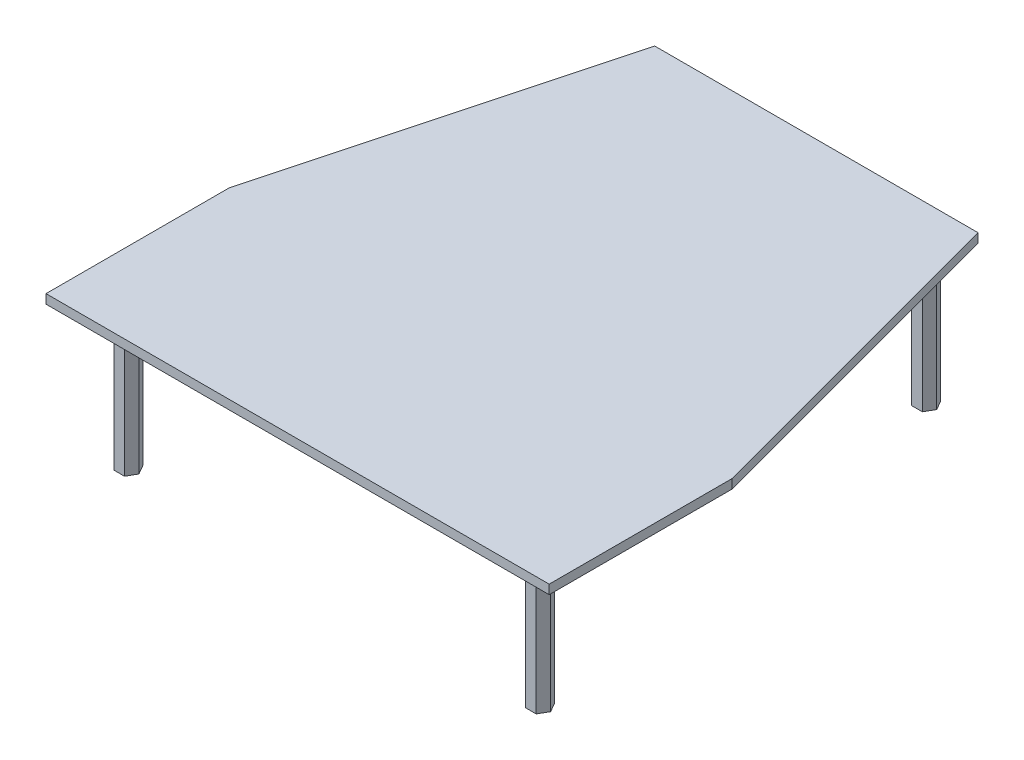
SolidWorks part; units mm, degrees
ref_plane "前视基准面" through (0, 0, 0) normal (0, 0, 1) x (1, 0, 0)
ref_plane "上视基准面" through (0, 0, 0) normal (0, 1, 0) x (1, 0, 0)
ref_plane "右视基准面" through (0, 0, 0) normal (1, 0, 0) x (0, 0, -1)
sketch "草图1" plane through (0, 0, 0) normal (0, 1, 0) x (1, 0, 0)
  line L0 (0, 0) -> (0, 262.6348) construction
  line L2 (-55, 0) -> (-55, 40)
  line L3 (-55, 40) -> (-35.3298, 113.4104)
  line L4 (-35.3298, 113.4104) -> (35.3298, 113.4104)
  line L15 (55, 40) -> (35.3298, 113.4104)
  line L16 (55, 0) -> (55, 40)
  line L17 (-55, 0) -> (55, 0)
  dimension "D1" = 15
  dimension "D3" = 110
  dimension "D4" = 76
  dimension "D5" = 40
extrude "凸台-拉伸1" add sketch "草图1" along normal mid plane 2
sketch "草图2" plane through (0, -1, 0) normal (0, -1, 0) x (1, 0, 0)
  line L0 (0, 0) -> (0, -113.4104) construction
  line L1 (-42.6906, -8) -> (-43.8453, -6)
  line L2 (-43.8453, -6) -> (-46.1547, -6)
  line L3 (-46.1547, -6) -> (-47.3094, -8)
  line L4 (-47.3094, -8) -> (-46.1547, -10)
  line L5 (-46.1547, -10) -> (-43.8453, -10)
  line L6 (-43.8453, -10) -> (-42.6906, -8)
  line L7 (-27.6906, -107.4104) -> (-28.8453, -105.4104)
  line L8 (-28.8453, -105.4104) -> (-31.1547, -105.4104)
  line L9 (-31.1547, -105.4104) -> (-32.3094, -107.4104)
  line L10 (-32.3094, -107.4104) -> (-31.1547, -109.4104)
  line L11 (-31.1547, -109.4104) -> (-28.8453, -109.4104)
  line L12 (-28.8453, -109.4104) -> (-27.6906, -107.4104)
  line L13 (35.3298, -113.4104) -> (-35.3298, -113.4104) construction
  line L14 (28.8453, -109.4104) -> (27.6906, -107.4104)
  line L15 (31.1547, -109.4104) -> (28.8453, -109.4104)
  line L16 (32.3094, -107.4104) -> (31.1547, -109.4104)
  line L17 (31.1547, -105.4104) -> (32.3094, -107.4104)
  line L18 (28.8453, -105.4104) -> (31.1547, -105.4104)
  line L19 (27.6906, -107.4104) -> (28.8453, -105.4104)
  line L20 (43.8453, -10) -> (42.6906, -8)
  line L21 (46.1547, -10) -> (43.8453, -10)
  line L22 (47.3094, -8) -> (46.1547, -10)
  line L23 (46.1547, -6) -> (47.3094, -8)
  line L24 (43.8453, -6) -> (46.1547, -6)
  line L25 (42.6906, -8) -> (43.8453, -6)
  circle A0 centre (-45, -8) radius 2 construction
  circle A1 centre (-30, -107.4104) radius 2 construction
  circle A2 centre (30, -107.4104) radius 2 construction
  circle A3 centre (45, -8) radius 2 construction
  point P19 (0, -113.4104)
  dimension "D1" = 4
  dimension "D4" = 4
  dimension "D2" = 45
  dimension "D3" = 8
  dimension "D5" = 30
  dimension "D6" = 6
extrude "凸台-拉伸2" add sketch "草图2" along normal blind 30
